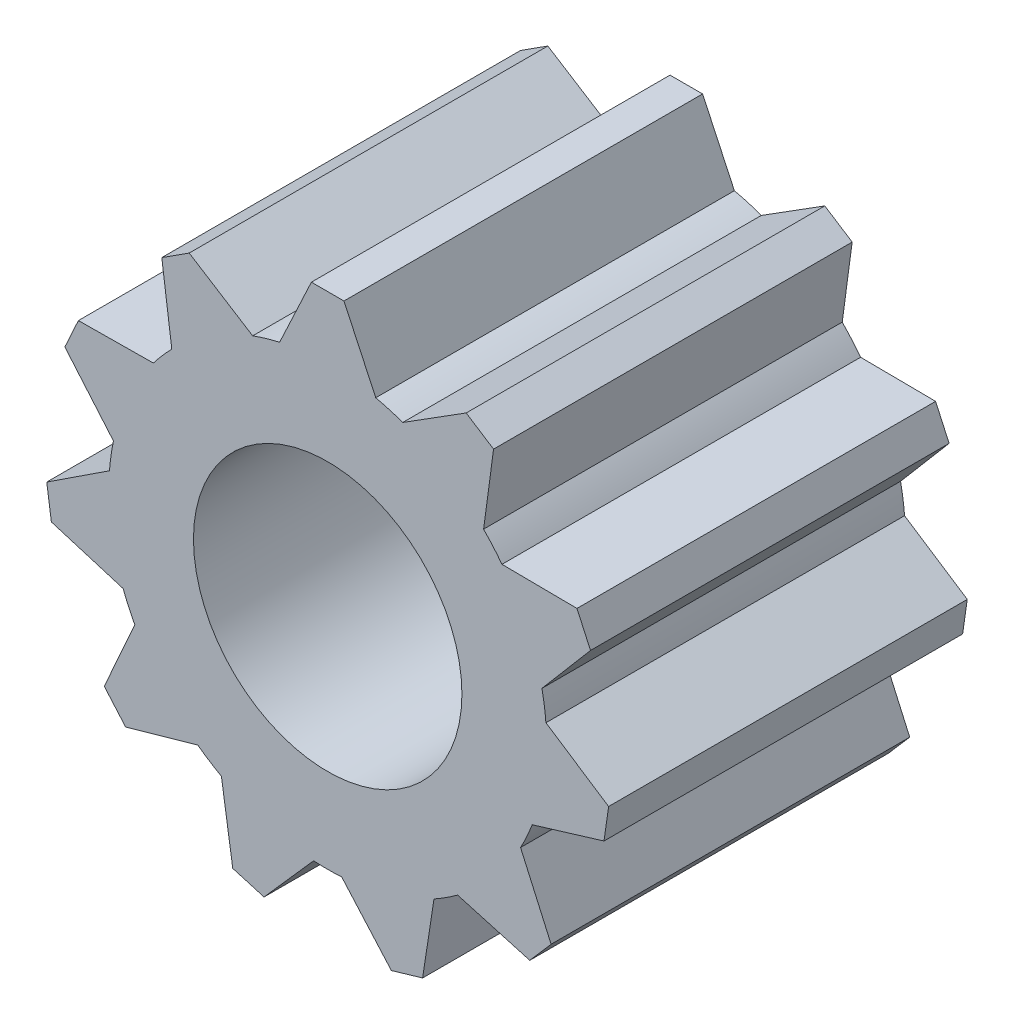
SolidWorks part; units mm, degrees
ref_plane "Front Plane" through (0, 0, 0) normal (0, 0, 1) x (1, 0, 0)
ref_plane "Top Plane" through (0, 0, 0) normal (0, 1, 0) x (1, 0, 0)
ref_plane "Right Plane" through (0, 0, 0) normal (1, 0, 0) x (0, 0, -1)
sketch "Sketch1" plane through (0, 0, 0) normal (0, 0, 1) x (1, 0, 0)
  line L1 (-9.65, 42.8756) -> (-3.2701, 56.5141)
  line L2 (31.2984, 30.8521) -> (33.3048, 45.7747)
  line L3 (9.65, 42.8756) -> (3.2701, 56.5141)
  line L4 (-3.2701, 56.5141) -> (3.2701, 56.5141)
  line L5 (27.8029, 49.3106) -> (33.3048, 45.7747)
  line L6 (15.0622, 41.2864) -> (27.8029, 49.3106)
  line L7 (43.0097, 9.0332) -> (52.7654, 20.5022)
  line L8 (50.0486, 26.4514) -> (52.7654, 20.5022)
  line L9 (34.9922, 26.5891) -> (50.0486, 26.4514)
  line L10 (41.0658, -15.6536) -> (55.4735, -11.2796)
  line L11 (56.4042, -4.806) -> (55.4735, -11.2796)
  line L12 (43.8125, 3.4499) -> (56.4042, -4.806)
  line L13 (26.0838, -35.3705) -> (40.569, -39.4802)
  line L14 (44.8519, -34.5375) -> (40.569, -39.4802)
  line L15 (38.7226, -20.7846) -> (44.8519, -34.5375)
  line L16 (2.8204, -43.8575) -> (12.7842, -55.1461)
  line L17 (19.0595, -53.3036) -> (12.7842, -55.1461)
  line L18 (21.3385, -38.4201) -> (19.0595, -53.3036)
  line L19 (-21.3385, -38.4201) -> (-19.0595, -53.3036)
  line L20 (-12.7842, -55.1461) -> (-19.0595, -53.3036)
  line L21 (-2.8204, -43.8575) -> (-12.7842, -55.1461)
  line L22 (-38.7226, -20.7846) -> (-44.8519, -34.5375)
  line L23 (-40.569, -39.4802) -> (-44.8519, -34.5375)
  line L24 (-26.0838, -35.3705) -> (-40.569, -39.4802)
  line L25 (-43.8125, 3.4499) -> (-56.4042, -4.806)
  line L26 (-55.4735, -11.2796) -> (-56.4042, -4.806)
  line L27 (-41.0658, -15.6536) -> (-55.4735, -11.2796)
  line L28 (-34.9922, 26.5891) -> (-50.0486, 26.4514)
  line L29 (-52.7654, 20.5022) -> (-50.0486, 26.4514)
  line L30 (-43.0097, 9.0332) -> (-52.7654, 20.5022)
  line L31 (-15.0622, 41.2864) -> (-27.8029, 49.3106)
  line L32 (-33.3048, 45.7747) -> (-27.8029, 49.3106)
  line L33 (-31.2984, 30.8521) -> (-33.3048, 45.7747)
  arc A0 (-9.65, 42.8756) -> (-15.0622, 41.2864) centre (0, 0) ccw
  arc A1 (-31.2984, 30.8521) -> (-34.9922, 26.5891) centre (0, 0) ccw
  arc A2 (15.0622, 41.2864) -> (9.65, 42.8756) centre (0, 0) ccw
  arc A3 (34.9922, 26.5891) -> (31.2984, 30.8521) centre (0, 0) ccw
  arc A4 (43.8125, 3.4499) -> (43.0097, 9.0332) centre (0, 0) ccw
  arc A5 (38.7226, -20.7846) -> (41.0658, -15.6536) centre (0, 0) ccw
  arc A6 (21.3385, -38.4201) -> (26.0838, -35.3705) centre (0, 0) ccw
  arc A7 (-2.8204, -43.8575) -> (2.8204, -43.8575) centre (0, 0) ccw
  arc A8 (-26.0838, -35.3705) -> (-21.3385, -38.4201) centre (0, 0) ccw
  arc A9 (-41.0658, -15.6536) -> (-38.7226, -20.7846) centre (0, 0) ccw
  arc A10 (-43.0097, 9.0332) -> (-43.8125, 3.4499) centre (0, 0) ccw
  circle A11 centre (0, 0) radius 26.9487
  point P6 (0, 43.9481)
  point P50 (0, 0)
  dimension "D1" = 11
extrude "Boss-Extrude2" add sketch "Sketch1" along normal blind 72
